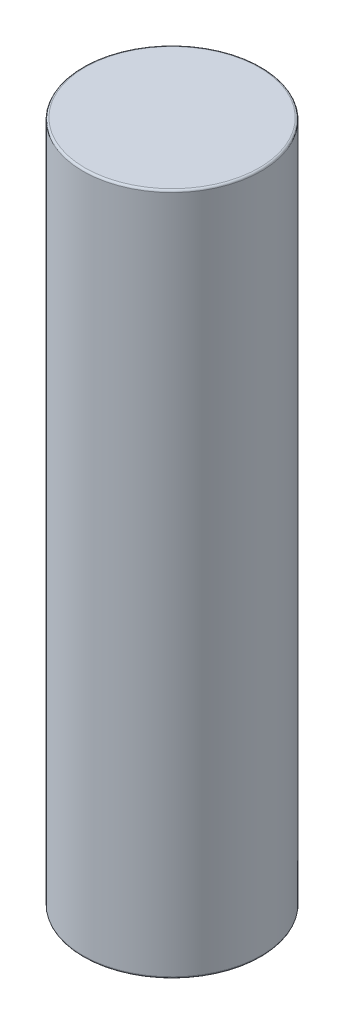
SolidWorks part; units mm, degrees
ref_plane "Alzado" through (0, 0, 0) normal (0, 0, 1) x (1, 0, 0)
ref_plane "Planta" through (0, 0, 0) normal (0, 1, 0) x (1, 0, 0)
ref_plane "Vista lateral" through (0, 0, 0) normal (1, 0, 0) x (0, 0, -1)
sketch "Croquis1" plane through (0, 0, 0) normal (0, 1, 0) x (1, 0, 0)
  circle A0 centre (0, 0) radius 9
  dimension "D1" = 18
extrude "Saliente-Extruir1" add sketch "Croquis1" along normal blind 69
fillet "Redondeo1" radius 0.2 2 edges at (0, 69, 9) (0, 0, 9)
